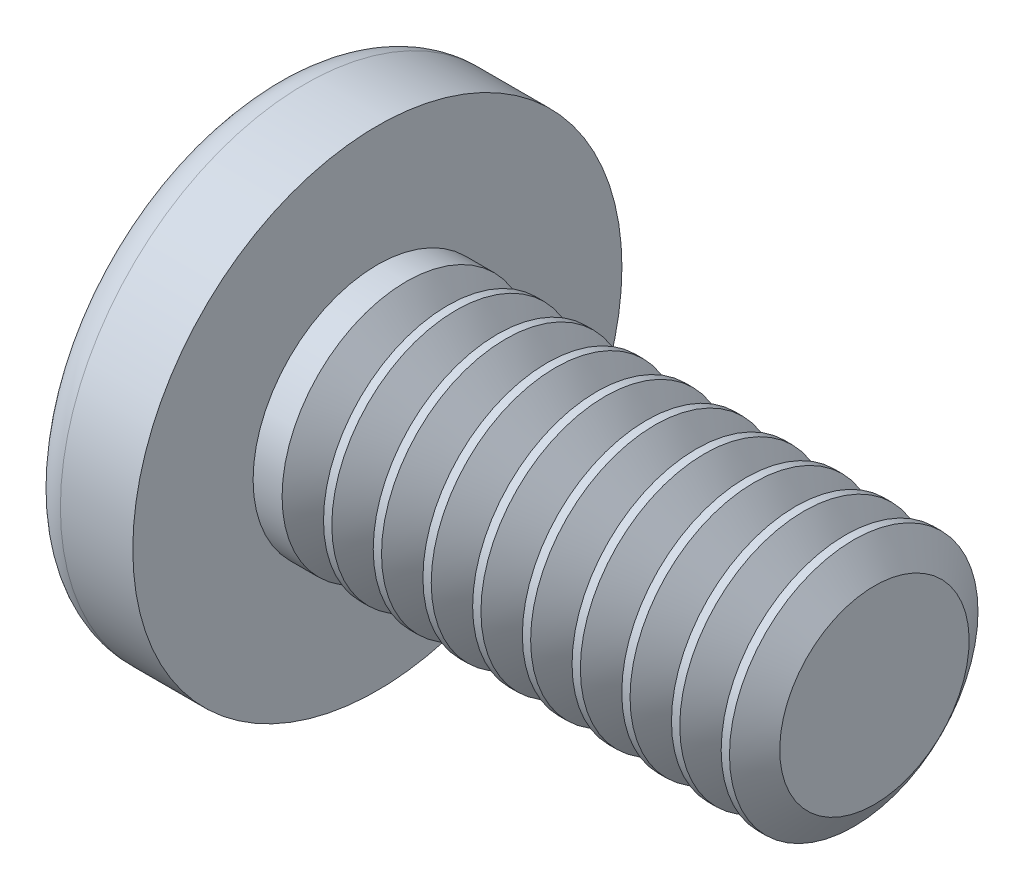
SolidWorks part; units mm, degrees
ref_plane "Plane1" through (0, 0, 0) normal (0, 0, 1) x (1, 0, 0)
ref_plane "Plane2" through (0, 0, 0) normal (0, 1, 0) x (1, 0, 0)
ref_plane "Plane3" through (0, 0, 0) normal (1, 0, 0) x (0, 0, -1)
sketch "BodySke" plane through (0, 0, 0) normal (0, 0, 1) x (1, 0, 0)
  line L0 (4.445, 3.175) -> (4.445, 6.2484)
  line L1 (5.08, 6.35) -> (5.08, -3.175) construction
  line L2 (-25.4, 0) -> (127, 0) construction
  line L3 (17.145, 0) -> (0, 0)
  line L4 (4.445, 3.175) -> (17.145, 3.175)
  line L5 (17.145, 3.175) -> (17.145, 0)
  line L6 (2.5951, 6.2484) -> (4.445, 6.2484)
  line L7 (4.445, -3.175) -> (17.145, -3.175) construction
  line L8 (4.445, 6.35) -> (4.445, -3.175) construction
  arc A0 (1.8697, 5.8733) -> (0, 0) centre (10.16, 0) ccw
  arc A2 (1.8697, 5.8733) -> (2.5951, 6.2484) centre (2.5951, 5.3594) cw
  dimension "Head_crown_rad" = 10.16
  dimension "Head_fillet_rad" = 0.889
  dimension "Diameter" = 6.35
  dimension "Length" = 12.7
  dimension "Head_ht" = 4.445
  dimension "Head_dia" = 12.4968
  dimension "Advance" = 1.27
  dimension "Thread_nom" = 12.7
revolve "Base-Revolve" add sketch "BodySke" angle 360 about L2
cosmetic thread "ThreadCosmetic" [suppressed] parameters "Thread_length"=11.43, "Thread_minor"=4.8387
sketch "Sketch3" plane through (0, 0, 0) normal (1, 0, 0) x (0, 0, -1)
  line L0 (0.7366, -4.0386) -> (-0.7366, -4.0386)
  line L1 (0.7366, -4.0386) -> (0.7366, 4.0386)
  line L2 (-0.7366, 4.0386) -> (0.7366, 4.0386)
  line L3 (-0.7366, 4.0386) -> (-0.7366, -4.0386)
  dimension "Cross_dia" = 8.0772
  dimension "D1" = 4.0386
  dimension "Cross_width" = 1.4732
  dimension "D2" = 0.7366
ref_plane "Plane4" through (4.572, 0, 0) normal (1, 0, 0) x (0, 0, -1)
sketch "Sketch4" plane through (4.572, 0, 0) normal (1, 0, 0) x (0, 0, -1)
  line L0 (0.3683, -0.3683) -> (-0.3683, -0.3683)
  line L1 (0.3683, -0.3683) -> (0.3683, 0.3683)
  line L2 (-0.3683, 0.3683) -> (0.3683, 0.3683)
  line L3 (-0.3683, 0.3683) -> (-0.3683, -0.3683)
  dimension "D2" = 0.7366
  dimension "D1" = 0.7366
  dimension "D3" = 0.3683
  dimension "D4" = 0.3683
loft "Cut-Loft1" cut profiles "Sketch3", "Sketch4"
pattern_circular "CirPattern1" count 2 every 90 about axis through (0, 0, 0) along (1, 0, 0) of "Cut-Loft1"
sketch "ThdSchSke" plane through (0, 0, 0) normal (0, 0, 1) x (1, 0, 0)
  line L0 (5.715, -2.4193) -> (5.1859, -3.175)
  line L1 (5.715, -2.4193) -> (6.2441, -3.175)
  line L2 (6.2441, -3.175) -> (6.2441, -3.9687)
  line L3 (-3.175, 0) -> (5.1513, 0) construction
  line L5 (6.2441, -3.9687) -> (5.1859, -3.9688)
  line L6 (5.1859, -3.9688) -> (5.1859, -3.175)
  dimension "Diameter" = 6.35
  dimension "SideAngle" = 55
  dimension "VeeAngle" = 70
  dimension "Thread_minor" = 4.8387
  dimension "Overcut" = 7.9375
  dimension "Start" = 5.715
revolve "ThreadSchematic" cut sketch "ThdSchSke" angle 360 about L3
pattern_linear "ThdSchPat" count 10 spacing 1.27 along (1, 0, 0) of "ThreadSchematic"
equation "\"D1@Sketch3\" = \"Cross_dia@Sketch3\" / 2"
equation "\"D2@Sketch3\" = \"Cross_width@Sketch3\" / 2"
equation "\"D1@Sketch4\" = \"Cross_width@Sketch3\" *.5"
equation "\"D2@Sketch4\" = \"D1@Sketch4\""
equation "\"D3@Sketch4\" = \"D1@Sketch4\" / 2"
equation "\"D4@Sketch4\" = \"D2@Sketch4\" / 2"
equation "\"Thread_length@ThreadCosmetic\" = ((sgn( (\"Length@BodySke\" - \"Advance@BodySke\" ) - \"Thread_nom@BodySke\" )-1)*( (\"Length@BodySke\" - \"Advance@BodySke\" ) - \"Thread_nom@BodySke\" ))/-2+ \"Thread_nom@BodySke\""
equation "\"Thread_minor@ThdSchSke\" = \"Thread_minor@ThreadCosmetic\""
equation "\"Diameter@ThdSchSke\" = \"Diameter@BodySke\""
equation "\"Overcut@ThdSchSke\" = \"Diameter@BodySke\" * 1.25"
equation "\"Start@ThdSchSke\" = \"Head_ht@BodySke\" + \"Length@BodySke\" - \"Thread_length@ThreadCosmetic\"  '---Non-countersunk---"
equation "\"Num_threads@ThdSchPat\" = int( \"Thread_length@ThreadCosmetic\" / \"Advance@BodySke\" + 0.999 )  + 1"
equation "\"Advance@ThdSchPat\" = \"Thread_length@ThreadCosmetic\" /  (\"Num_threads@ThdSchPat\" - 1) 'relax it"
